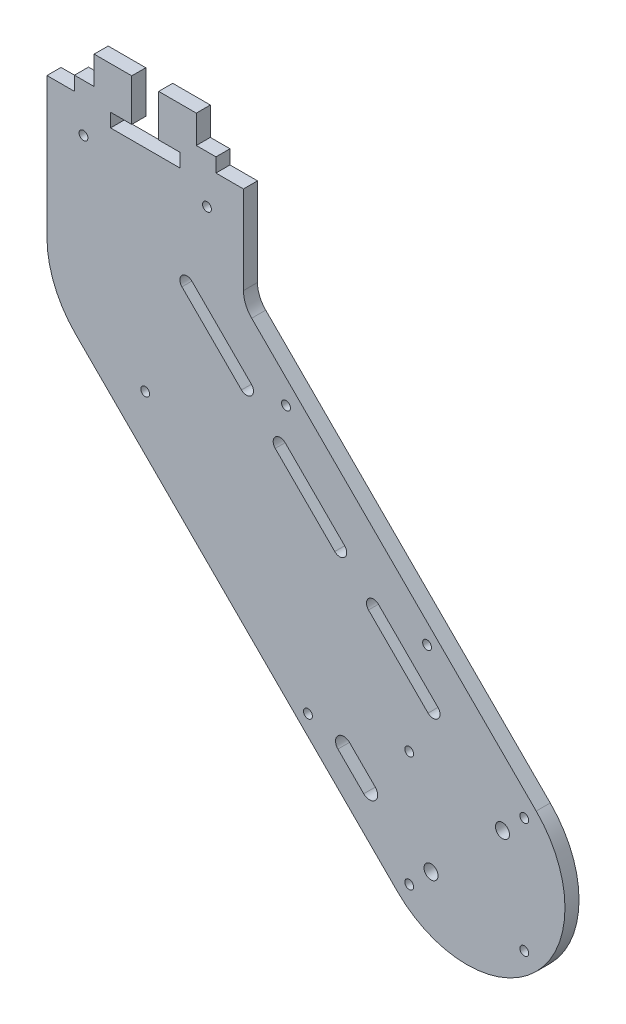
SolidWorks part; units mm, degrees
ref_plane "Front Plane" through (0, 0, 0) normal (0, 0, 1) x (1, 0, 0)
ref_plane "Top Plane" through (0, 0, 0) normal (0, 1, 0) x (1, 0, 0)
ref_plane "Right Plane" through (0, 0, 0) normal (1, 0, 0) x (0, 0, -1)
sketch "Sketch1" plane through (0, 0, 0) normal (0, 0, 1) x (1, 0, 0)
  line L0 (0, 0) -> (35, 0) construction
  line L1 (0, 0) -> (0, 35) construction
  line L2 (0, 0) -> (24.7487, 24.7487) construction
  line L3 (0, 0) -> (-24.7487, -24.7487) construction
  line L4 (-24.7487, -24.7487) -> (-139.3, 89.8026)
  line L5 (0, 0) -> (24.7487, -24.7487) construction
  line L6 (-139.3, 89.8026) -> (-114.5513, 114.5513) construction
  line L7 (24.7487, 24.7487) -> (-54.6728, 104.1703)
  line L8 (-43.834, 10.6132) -> (-34.6417, 1.4208) construction
  line L11 (-114.5513, 114.5513) -> (0, 0) construction
  line L12 (-41.7764, 12.6709) -> (-32.584, 3.4785)
  line L15 (-31.8198, 38.8909) -> (-10.6066, 60.1041) construction
  line L16 (-45.8917, 8.5555) -> (-36.6993, -0.6369)
  line L19 (-31.8198, 38.8909) -> (-60.1041, 10.6066) construction
  line L20 (-33.234, 58.6899) -> (-12.0208, 37.4767) construction
  line L26 (-64.3969, 105.3087) -> (-109.6016, 60.1041) construction
  line L30 (-31.4663, 60.4576) -> (-10.253, 39.2444)
  line L33 (-74.2462, 74.2462) -> (-49.4975, 98.9949) construction
  line L34 (-70.3571, 70.3571) -> (-45.6084, 95.1059) construction
  line L37 (-35.0018, 56.9221) -> (-13.7886, 35.7089)
  line L40 (-114.5513, 114.5513) -> (-207.3962, 114.5513) construction
  line L41 (-149.5513, 114.5513) -> (-149.5513, 164.5513)
  line L42 (-114.5513, 114.5513) -> (-8.6743, 114.5513) construction
  line L43 (-79.5513, 133.1909) -> (-79.5513, 165.6653)
  line L44 (-114.5513, 114.5513) -> (-79.5513, 149.5513) construction
  line L45 (-54.6728, 104.1703) -> (-76.6224, 126.1198)
  line L46 (-114.5513, 114.5513) -> (-146.8871, 101.1574) construction
  line L47 (-146.8871, 101.1574) -> (-49.8797, 141.3391) construction
  line L48 (-114.5513, 114.5513) -> (-114.5513, 82.9763) construction
  line L49 (-132.7513, 174.5513) -> (-119.3513, 174.5513) construction
  line L50 (-79.5513, 165.6653) -> (-79.5513, 174.5513)
  line L51 (-119.3513, 169.5513) -> (-109.7513, 169.5513)
  line L52 (-114.5513, 114.5513) -> (-114.5513, 174.5513) construction
  line L53 (-119.3513, 174.5513) -> (-132.7513, 174.5513)
  line L54 (-126.9013, 164.5513) -> (-102.2013, 164.5513)
  line L55 (-126.9013, 164.5513) -> (-126.9013, 159.7013)
  line L56 (-126.9013, 159.7013) -> (-102.2013, 159.7013)
  line L57 (-102.2013, 164.5513) -> (-102.2013, 159.7013)
  line L58 (-139.7513, 169.5513) -> (-132.7513, 169.5513) construction
  line L59 (-66.468, 91.9239) -> (-45.2548, 70.7107) construction
  line L60 (-132.7513, 174.5513) -> (-132.7513, 169.5513) construction
  line L61 (-119.3513, 169.5513) -> (-119.3513, 174.5513)
  line L62 (-114.5513, 174.5513) -> (-96.3513, 174.5513) construction
  line L63 (-114.5513, 159.7013) -> (-114.5513, 164.5513) construction
  line L64 (-126.9013, 162.1263) -> (-102.2013, 162.1263) construction
  line L65 (-149.5513, 164.5513) -> (-79.5513, 164.5513) construction
  line L66 (-132.7513, 169.5513) -> (-139.7513, 169.5513)
  line L67 (-139.7513, 169.5513) -> (-139.7513, 164.5513)
  line L68 (-139.7513, 164.5513) -> (-149.5513, 164.5513)
  line L69 (-132.7513, 169.5513) -> (-132.7513, 174.5513)
  line L70 (-109.7513, 169.5513) -> (-109.7513, 174.5513)
  line L71 (-109.7513, 174.5513) -> (-96.3513, 174.5513)
  line L72 (-96.3513, 169.5513) -> (-96.3513, 174.5513)
  line L73 (-96.3513, 169.5513) -> (-89.3513, 169.5513)
  line L74 (-89.3513, 169.5513) -> (-89.3513, 164.5513)
  line L75 (-89.3513, 164.5513) -> (-79.5513, 164.5513)
  line L76 (-119.3513, 169.5513) -> (-109.7513, 169.5513) construction
  line L77 (-96.3513, 169.5513) -> (-89.3513, 169.5513) construction
  line L78 (-64.7003, 93.6916) -> (-43.4871, 72.4784)
  line L79 (-68.2358, 90.1561) -> (-47.0226, 68.9429)
  line L80 (-99.7021, 125.1579) -> (-78.4889, 103.9447) construction
  line L81 (-97.9343, 126.9257) -> (-76.7211, 105.7125)
  line L82 (-101.4698, 123.3901) -> (-80.2566, 102.1769)
  line L83 (-119.3513, 169.5513) -> (-119.3513, 164.5513)
  line L84 (-109.7513, 169.5513) -> (-109.7513, 164.5513)
  arc A1 (-24.7487, -24.7487) -> (24.7487, 24.7487) centre (0, 0) ccw
  circle A3 centre (20.5061, -20.5061) radius 1.575
  circle A4 centre (-20.5061, -20.5061) radius 1.575
  circle A5 centre (-20.5061, 20.5061) radius 1.575
  circle A6 centre (20.5061, 20.5061) radius 1.575
  circle A15 centre (-14.1421, 56.5685) radius 1.575
  circle A16 centre (-56.5685, 14.1421) radius 1.575
  circle A17 centre (-64.3969, 105.3087) radius 1.575
  arc A29 (-149.5513, 114.5513) -> (-139.3, 89.8026) centre (-114.5513, 114.5513) ccw
  arc A31 (-76.6224, 126.1198) -> (-79.5513, 133.1909) centre (-69.5513, 133.1909) cw
  circle A36 centre (-114.5513, 84.5513) radius 1.575
  circle A37 centre (-136.5513, 152.5513) radius 1.575
  circle A38 centre (-92.5513, 152.5513) radius 1.575
  circle A43 centre (12.7279, 12.7279) radius 2.5
  circle A44 centre (-12.7279, -12.7279) radius 2.5
  arc A45 (-41.7764, 12.6709) -> (-45.8917, 8.5555) centre (-43.834, 10.6132) ccw
  arc A46 (-36.6993, -0.6369) -> (-32.584, 3.4785) centre (-34.6417, 1.4208) ccw
  arc A49 (-31.4663, 60.4576) -> (-35.0018, 56.9221) centre (-33.234, 58.6899) ccw
  arc A50 (-13.7886, 35.7089) -> (-10.253, 39.2444) centre (-12.0208, 37.4767) ccw
  arc A51 (-64.7003, 93.6916) -> (-68.2358, 90.1561) centre (-66.468, 91.9239) ccw
  arc A52 (-47.0226, 68.9429) -> (-43.4871, 72.4784) centre (-45.2548, 70.7107) ccw
  arc A53 (-97.9343, 126.9257) -> (-101.4698, 123.3901) centre (-99.7021, 125.1579) ccw
  arc A54 (-80.2566, 102.1769) -> (-76.7211, 105.7125) centre (-78.4889, 103.9447) ccw
  point P23 (0, 0)
  point P24 (-39.2378, 6.017)
  point P31 (-22.6274, 48.0833)
  point P40 (-55.8614, 81.3173)
  point P46 (-89.0955, 114.5513)
  point P52 (0, 0)
  point P107 (-79.5513, 129.0488)
  point P123 (-114.5513, 162.1263)
  dimension "D2" = 70
  dimension "D7" = 3.15
  dimension "D12" = 2.91
  dimension "D15" = 2.5
  dimension "D20" = 3.15
  dimension "D22" = 3.15
  dimension "D25" = 30
  dimension "D29" = 17
  dimension "D30" = 2.5
  dimension "D35" = 35.1835
  dimension "D36" = 32.1163
  dimension "D37" = 10
  dimension "D41" = 3.15
  dimension "D43" = 3.15
  dimension "D61" = 18
  dimension "D62" = 5
  dimension "D14" = 30
  dimension "D26" = 2.5
  dimension "D3" = 45
  dimension "D4" = 180
  dimension "D5" = 162
  dimension "D8" = 29
  dimension "D10" = 35
  dimension "D11" = 25.5
  dimension "D13" = 13
  dimension "D16" = 35
  dimension "D17" = 18
  dimension "D18" = 18
  dimension "D19" = 17
  dimension "D21" = 5
  dimension "D23" = 6.071
  dimension "D24" = 70
  dimension "D27" = 18
  dimension "D28" = 30
  dimension "D32" = 70
  dimension "D33" = 35
  dimension "D34" = 180
  dimension "D42" = 30
  dimension "D44" = 13
  dimension "D45" = 38
  dimension "D47" = 18.2
  dimension "D48" = 12.425
  dimension "D49" = 10
  dimension "D50" = 24.7
  dimension "D51" = 5
  dimension "D52" = 13.4
  dimension "D53" = 5
  dimension "D54" = 25.2
  dimension "D9" = 4
extrude "Boss-Extrude1" add sketch "Sketch1" against normal blind 5
sketch "Sketch3" plane through (0, 0, 0) normal (0, 0, 1) x (1, 0, 0)
  line L0 (-132.7513, 174.5513) -> (-132.7513, 179.5513)
  line L1 (-132.7513, 179.5513) -> (-119.3513, 179.5513)
  line L2 (-119.3513, 179.5513) -> (-119.3513, 174.5513)
  line L3 (-109.7513, 174.5513) -> (-109.7513, 179.5513)
  line L4 (-109.7513, 179.5513) -> (-96.3513, 179.5513)
  line L5 (-96.3513, 179.5513) -> (-96.3513, 174.5513)
  line L6 (-96.3513, 174.5513) -> (-109.7513, 174.5513)
  line L7 (-119.3513, 174.5513) -> (-132.7513, 174.5513)
extrude "Boss-Extrude2" add sketch "Sketch3" against normal blind 5
